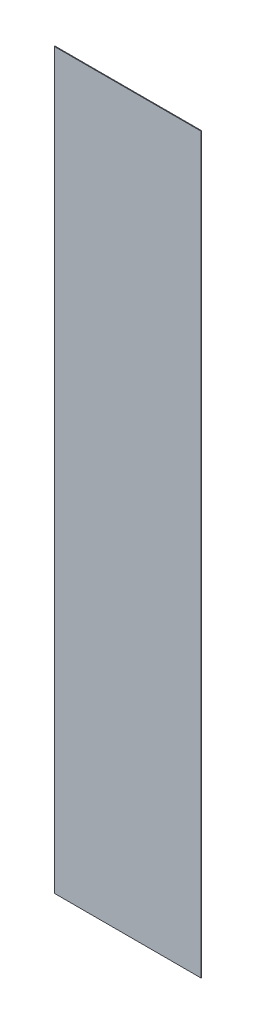
SolidWorks part; units mm, degrees
ref_plane "Alzado" through (0, 0, 0) normal (0, 0, 1) x (1, 0, 0)
ref_plane "Planta" through (0, 0, 0) normal (0, 1, 0) x (1, 0, 0)
ref_plane "Vista lateral" through (0, 0, 0) normal (1, 0, 0) x (0, 0, -1)
sketch "Croquis1" plane through (0, 0, 0) normal (0, 0, 1) x (1, 0, 0)
  line L1 (-200, 1000) -> (200, 1000)
  line L2 (-200, 1000) -> (-200, -1000)
  line L3 (-200, -1000) -> (200, -1000)
  line L4 (200, 1000) -> (200, -1000)
  line L5 (-200, 1000) -> (200, -1000) construction
  line L6 (-200, -1000) -> (200, 1000) construction
  point P0 (0, 0)
  dimension "D1" = 2000
  dimension "D2" = 400
extrude "Saliente-Extruir1" add sketch "Croquis1" along normal blind 1.9
